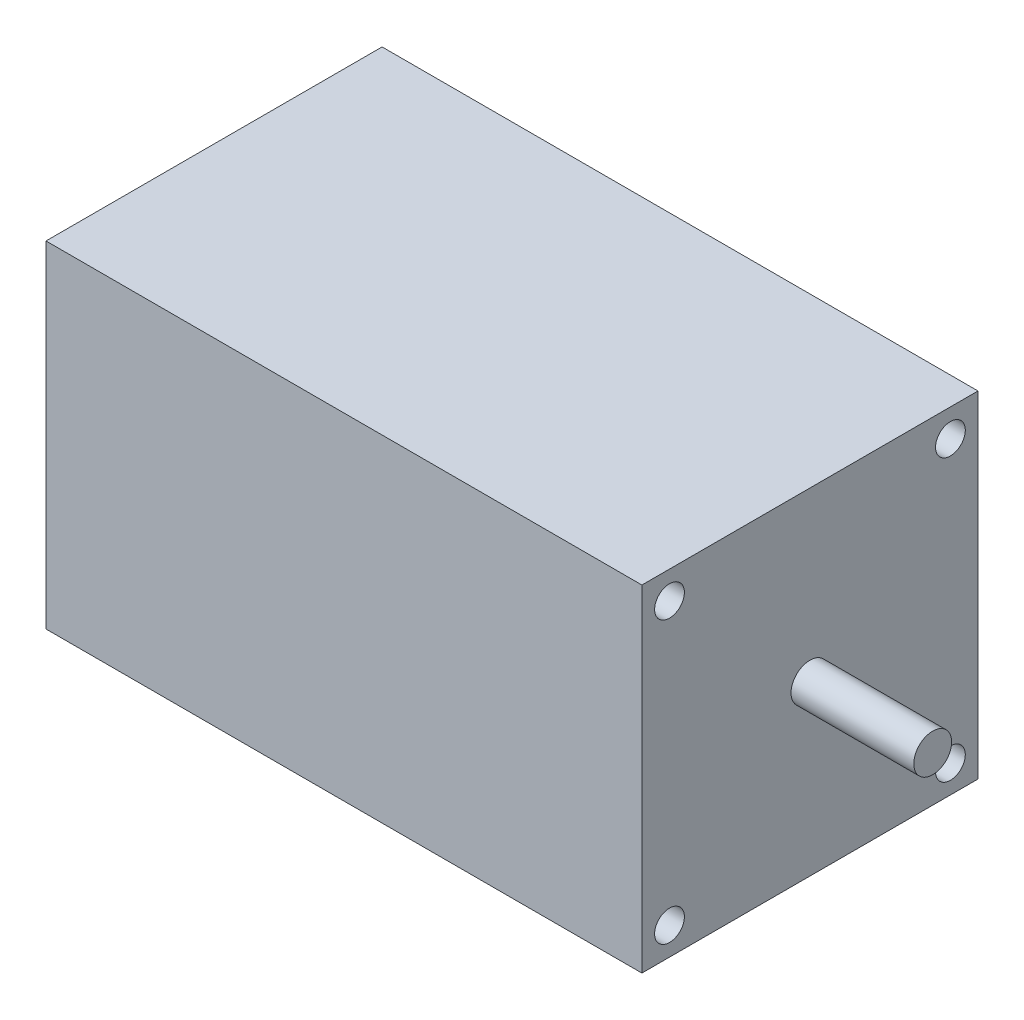
SolidWorks part; units mm, degrees
ref_plane "Front Plane" through (0, 0, 0) normal (0, 0, 1) x (1, 0, 0)
ref_plane "Top Plane" through (0, 0, 0) normal (0, 1, 0) x (1, 0, 0)
ref_plane "Right Plane" through (0, 0, 0) normal (1, 0, 0) x (0, 0, -1)
sketch "Sketch2" plane through (0, 0, 0) normal (1, 0, 0) x (0, 0, -1)
  line L1 (-28.2, -28.2) -> (28.2, -28.2)
  line L2 (-28.2, -28.2) -> (-28.2, 28.2)
  line L3 (-28.2, 28.2) -> (28.2, 28.2)
  line L4 (28.2, -28.2) -> (28.2, 28.2)
  line L5 (-28.2, -28.2) -> (28.2, 28.2) construction
  line L6 (-28.2, 28.2) -> (28.2, -28.2) construction
  point P0 (0, 0)
  dimension "D1" = 56.4
  dimension "D2" = 56.4
extrude "Boss-Extrude1" add sketch "Sketch2" against normal blind 100
sketch "Sketch3" plane through (0, 0, 0) normal (1, 0, 0) x (0, 0, -1)
  line L0 (-0.3946, 0) -> (-37.5858, 0) construction
  line L1 (0, 0) -> (0, -13.9867) construction
  circle A0 centre (-23.57, 23.57) radius 2.5
  circle A1 centre (23.57, 23.57) radius 2.5
  circle A2 centre (23.57, -23.57) radius 2.5
  circle A3 centre (-23.57, -23.57) radius 2.5
  point P9 (0, 21.8378)
  dimension "D3" = 5
  dimension "D1" = 23.57
  dimension "D2" = 23.57
extrude "Cut-Extrude1" cut sketch "Sketch3" against normal up to surface (100 mm away) up to face at (-100, 0, 0)
sketch "Sketch4" plane through (0, 0, 0) normal (1, 0, 0) x (0, 0, -1)
  circle A0 centre (0, 0) radius 3.175
  dimension "D1" = 6.35
extrude "Boss-Extrude2" add sketch "Sketch4" along normal blind 20.6
